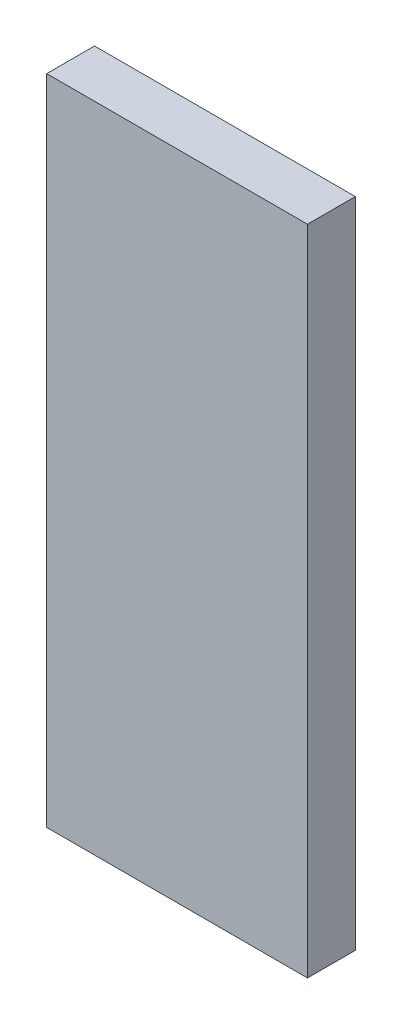
SolidWorks part; units mm, degrees
ref_plane "Front Plane" through (0, 0, 0) normal (0, 0, 1) x (1, 0, 0)
ref_plane "Top Plane" through (0, 0, 0) normal (0, 1, 0) x (1, 0, 0)
ref_plane "Right Plane" through (0, 0, 0) normal (1, 0, 0) x (0, 0, -1)
sketch "Sketch1" plane through (0, 0, 0) normal (0, 0, 1) x (1, 0, 0)
  line L1 (0, 0) -> (27.686, 0)
  line L2 (0, 0) -> (0, 69.3)
  line L3 (0, 69.3) -> (27.686, 69.3)
  line L4 (27.686, 0) -> (27.686, 69.3)
  dimension "D1" = 27.686
  dimension "D2" = 69.3
extrude "Boss-Extrude1" add sketch "Sketch1" along normal blind 5.08
equation "\"MDF\"= .2"
equation "\"Foamcore\"= .1"
equation "\"GMaterial\"= \"MDF\""
equation "\"CutDistance\" = .1"
equation "\"D1@Boss-Extrude1\"=\"GMaterial\""
